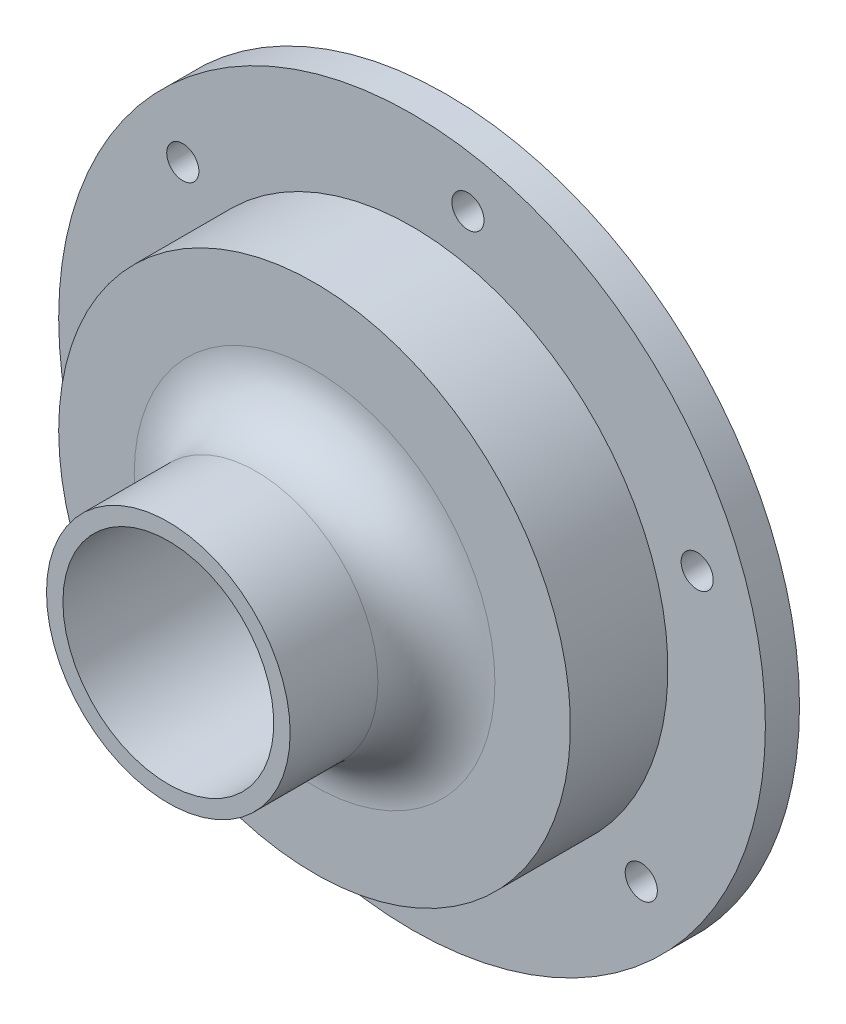
SolidWorks part; units mm, degrees
ref_plane "Front Plane" through (0, 0, 0) normal (0, 0, 1) x (1, 0, 0)
ref_plane "Top Plane" through (0, 0, 0) normal (0, 1, 0) x (1, 0, 0)
ref_plane "Right Plane" through (0, 0, 0) normal (1, 0, 0) x (0, 0, -1)
sketch "Sketch2" plane through (0, 0, 0) normal (0, 1, 0) x (1, 0, 0)
  line L0 (-72.5, 0) -> (72.5, 0) construction
  line L1 (-72.5, 0) -> (-72.5, -7)
  line L2 (-72.5, -7) -> (-52.5, -7)
  line L3 (-52.5, -7) -> (-52.5, -27)
  line L4 (-52.5, -27) -> (-25, -27)
  line L5 (-25, -27) -> (-25, -57)
  line L6 (-25, -57) -> (-21.63, -57)
  line L7 (-21.63, -57) -> (-21.63, 0)
  line L8 (-72.5, 0) -> (-21.63, 0)
  line L9 (0, 0) -> (0, -69.8441) construction
  dimension "D1" = 145
  dimension "D2" = 21.63
  dimension "D3" = 25
  dimension "D4" = 7
  dimension "D5" = 20
  dimension "D6" = 30
  dimension "D7" = 20
revolve "Revolve1" add sketch "Sketch2" angle 360 about L9
fillet "Fillet1" radius 12 1 edges at (-25, 0, 27)
hole_wizard "CBORE for M6 Hex Head Bolt1" positions "3DSketch1" profile "Sketch3" counterbore size "M6" standard "ISO" end condition through all
sketch3d "3DSketch1"
  point P0 (-47.0314, 40.3987, 0)
  dimension "D1" = 62
sketch "Sketch3" plane through (-47.0314, 40.3987, 0) normal (1, 0, 0) x (0, 1, 0)
  line L0 (0, 0) -> (0, 57)
  line L1 (0, 57) -> (3.3, 57)
  line L3 (3.3, 57) -> (3.3, 1)
  line L4 (3.3, 1) -> (7.2735, 1)
  line L5 (7.2735, 1) -> (7.2735, 0)
  line L7 (7.2735, 0) -> (0, 0)
  line L11 (0, -6.35) -> (0, 107.95) construction
  dimension "Thru Hole Dia." = 6.6
  dimension "Thru Hole Depth" = 57
  dimension "C'Bore Dia." = 14.547
  dimension "C'Bore Depth" = 1
pattern_circular "CirPattern1" count 6 over 360 about axis through (0, 0, 0) along (0, 0, 1) of "CBORE for M6 Hex Head Bolt1"
